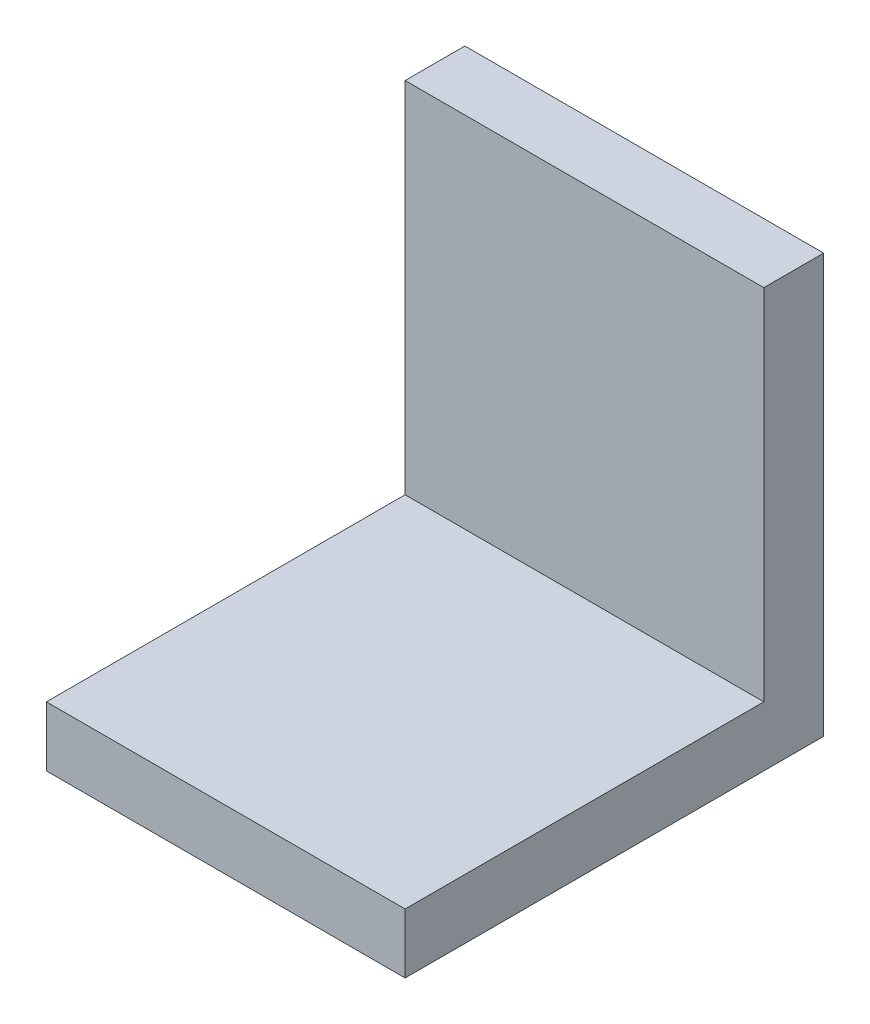
SolidWorks part; units mm, degrees
ref_plane "Front Plane" through (0, 0, 0) normal (0, 0, 1) x (1, 0, 0)
ref_plane "Top Plane" through (0, 0, 0) normal (0, 1, 0) x (1, 0, 0)
ref_plane "Right Plane" through (0, 0, 0) normal (1, 0, 0) x (0, 0, -1)
sketch "Sketch1" plane through (0, 0, 0) normal (1, 0, 0) x (0, 0, -1)
  line L0 (0, 0) -> (-35, 0)
  line L1 (-35, 0) -> (-35, 5)
  line L2 (-35, 5) -> (-5, 5)
  line L3 (-5, 5) -> (-5, 35)
  line L4 (-5, 35) -> (0, 35)
  line L5 (0, 35) -> (0, 0)
  dimension "D1" = 30
  dimension "D2" = 5
extrude "Boss-Extrude1" add sketch "Sketch1" along normal blind 30
